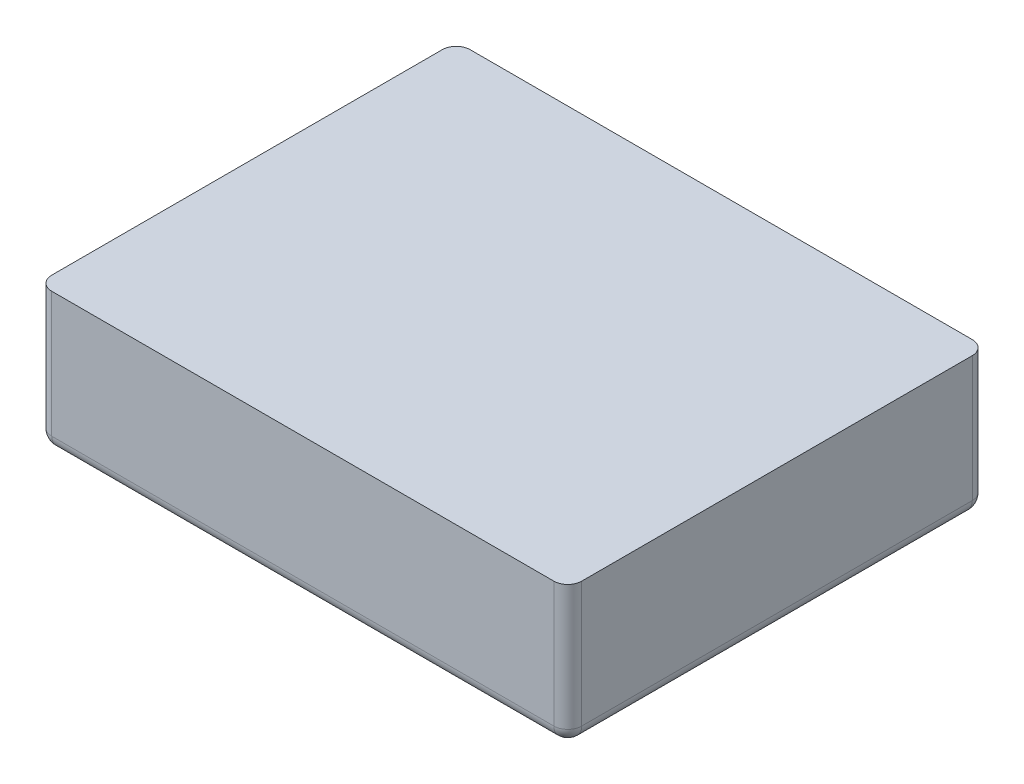
SolidWorks part; units mm, degrees
ref_plane "Front Plane" through (0, 0, 0) normal (0, 0, 1) x (1, 0, 0)
ref_plane "Top Plane" through (0, 0, 0) normal (0, 1, 0) x (1, 0, 0)
ref_plane "Right Plane" through (0, 0, 0) normal (1, 0, 0) x (0, 0, -1)
sketch "Sketch1" plane through (0, 0, 0) normal (0, 1, 0) x (1, 0, 0)
  line L1 (0, 0) -> (482.6, 0)
  line L2 (0, 0) -> (0, 381)
  line L3 (0, 381) -> (482.6, 381)
  line L4 (482.6, 0) -> (482.6, 381)
  dimension "D1" = 482.6
  dimension "D2" = 381
extrude "Boss-Extrude1" add sketch "Sketch1" against normal blind 127
fillet "Fillet1" radius 12.7 8 edges at (482.6, -63.5, -381) (0, -63.5, -381) (241.3, -127, -381) (0, -127, -190.5) (482.6, -127, -190.5) (241.3, -127, 0) (0, -63.5, 0) (482.6, -63.5, 0)
